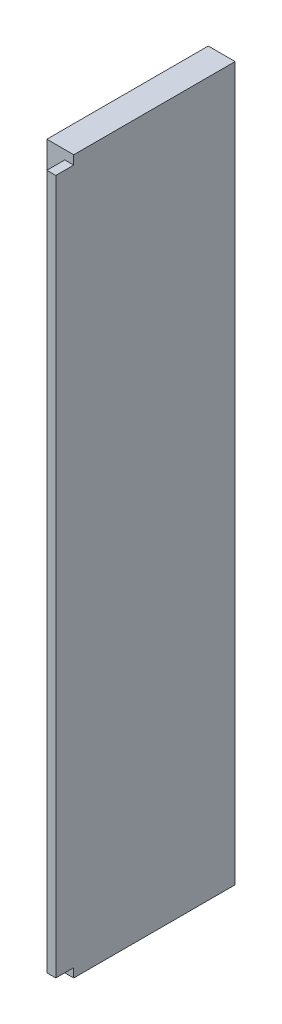
SolidWorks part; units mm, degrees
ref_plane "Front Plane" through (0, 0, 0) normal (0, 0, 1) x (1, 0, 0)
ref_plane "Top Plane" through (0, 0, 0) normal (0, 1, 0) x (1, 0, 0)
ref_plane "Right Plane" through (0, 0, 0) normal (1, 0, 0) x (0, 0, -1)
sketch "Sketch1" plane through (0, 0, 0) normal (0, 1, 0) x (1, 0, 0)
  line L0 (0, -16) -> (0, 16)
  line L1 (0, 16) -> (-4, 16)
  line L2 (-4, 16) -> (-4, 18)
  line L3 (-4, 18) -> (2, 18)
  line L4 (2, 18) -> (2, -18)
  line L5 (0, -18) -> (-4, -18)
  line L6 (-4, -18) -> (-4, -16)
  line L7 (-4, -16) -> (0, -16)
  line L8 (2, -18) -> (2, -22)
  line L9 (2, -22) -> (0, -22)
  line L10 (0, -22) -> (0, -18)
  point P4 (0, 0)
  point P13 (0, -24.5503)
  point P15 (0, 0)
  dimension "D1" = 32
  dimension "D2" = 2
  dimension "D3" = 4
  dimension "D4" = 2
  dimension "D5" = 4
extrude "Boss-Extrude1" add sketch "Sketch1" along normal blind 155
sketch "Sketch2" plane through (0, 155, 0) normal (0, 1, 0) x (1, 0, 0)
  line L1 (2, 18) -> (-4, 18)
  line L2 (2, 18) -> (2, -18)
  line L3 (2, -18) -> (-4, -18)
  line L4 (-4, 18) -> (-4, -18)
extrude "Boss-Extrude2" add sketch "Sketch2" along normal blind 2
sketch "Sketch3" plane through (0, 0, 0) normal (0, -1, 0) x (1, 0, 0)
  line L1 (2, -18) -> (-4, -18)
  line L2 (2, -18) -> (2, 18)
  line L3 (2, 18) -> (-4, 18)
  line L4 (-4, -18) -> (-4, 18)
extrude "Boss-Extrude3" add sketch "Sketch3" along normal blind 2
sketch "Sketch4" plane through (0, 0, 0) normal (0, 1, 0) x (1, 0, 0)
  line L0 (0, 16) -> (0, -16) construction
  line L1 (0, -12.5) -> (-3, -12.5)
  line L2 (0, -12.5) -> (0, -9.5)
  line L3 (0, -9.5) -> (-3, -9.5)
  line L4 (-3, -12.5) -> (-3, -9.5)
  line L5 (0, -9.5) -> (0, -5.1667) construction
  line L6 (0, -5.1667) -> (-3, -5.1667)
  line L7 (0, -5.1667) -> (0, -2.1667)
  line L8 (0, -2.1667) -> (-3, -2.1667)
  line L9 (-3, -5.1667) -> (-3, -2.1667)
  line L10 (0, 2.1667) -> (-3, 2.1667)
  line L11 (0, 2.1667) -> (0, 5.1667)
  line L12 (0, 5.1667) -> (-3, 5.1667)
  line L13 (-3, 2.1667) -> (-3, 5.1667)
  line L14 (0, 9.5) -> (-3, 9.5)
  line L15 (0, 9.5) -> (0, 12.5)
  line L16 (0, 12.5) -> (-3, 12.5)
  line L17 (-3, 9.5) -> (-3, 12.5)
  line L18 (0, -2.1667) -> (0, 2.1667) construction
  line L19 (0, 5.1667) -> (0, 9.5) construction
  line L20 (-4, -16) -> (-4, 16) construction
  point P18 (0, 0)
  dimension "D1" = 3
  dimension "D2" = 22
  dimension "D3" = 1
extrude "Cut-Extrude1" cut sketch "Sketch4" against normal up to next
